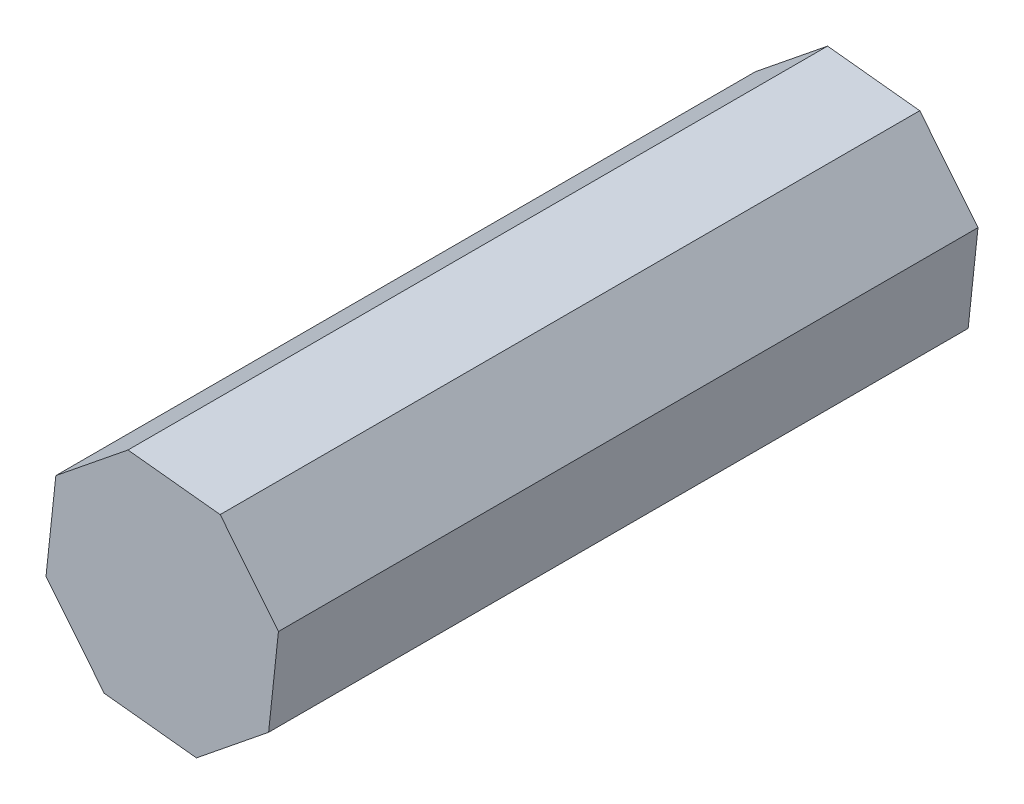
SolidWorks part; units mm, degrees
ref_plane "Front Plane" through (0, 0, 0) normal (0, 0, 1) x (1, 0, 0)
ref_plane "Top Plane" through (0, 0, 0) normal (0, 1, 0) x (1, 0, 0)
ref_plane "Right Plane" through (0, 0, 0) normal (1, 0, 0) x (0, 0, -1)
sketch "Esboço2" plane through (0, 0, 0) normal (0, 0, 1) x (1, 0, 0)
  line L1 (15.2073, -8.2862) -> (16.6124, 4.8939)
  line L2 (16.6124, 4.8939) -> (8.2862, 15.2073)
  line L3 (8.2862, 15.2073) -> (-4.8939, 16.6124)
  line L4 (-4.8939, 16.6124) -> (-15.2073, 8.2862)
  line L5 (-15.2073, 8.2862) -> (-16.6124, -4.8939)
  line L6 (-16.6124, -4.8939) -> (-8.2862, -15.2073)
  line L7 (-8.2862, -15.2073) -> (4.8939, -16.6124)
  line L8 (4.8939, -16.6124) -> (15.2073, -8.2862)
  circle A1 centre (0, 0) radius 16 construction
  dimension "D1" = 32
extrude "Ressalto-extrusão1" add sketch "Esboço2" along normal blind 100
sketch "Esboço1" plane through (0, 0, 0) normal (0, 0, 1) x (1, 0, 0)
  line L0 (0, 0) -> (15.2073, -8.2862) construction
  line L7 (10.9302, -5.9557) -> (11.9402, 3.5175)
  line L8 (11.9402, 3.5175) -> (5.9557, 10.9302)
  line L9 (5.9557, 10.9302) -> (-3.5175, 11.9402)
  line L10 (-3.5175, 11.9402) -> (-10.9302, 5.9557)
  line L11 (-10.9302, 5.9557) -> (-11.9402, -3.5175)
  line L12 (-11.9402, -3.5175) -> (-5.9557, -10.9302)
  line L13 (-5.9557, -10.9302) -> (3.5175, -11.9402)
  line L14 (3.5175, -11.9402) -> (10.9302, -5.9557)
  circle A0 centre (0, 0) radius 11.5 construction
  point P1 (0, 0)
  dimension "D1" = 23
extrude "Corte-extrusão1" cut sketch "Esboço1" along normal blind 20
